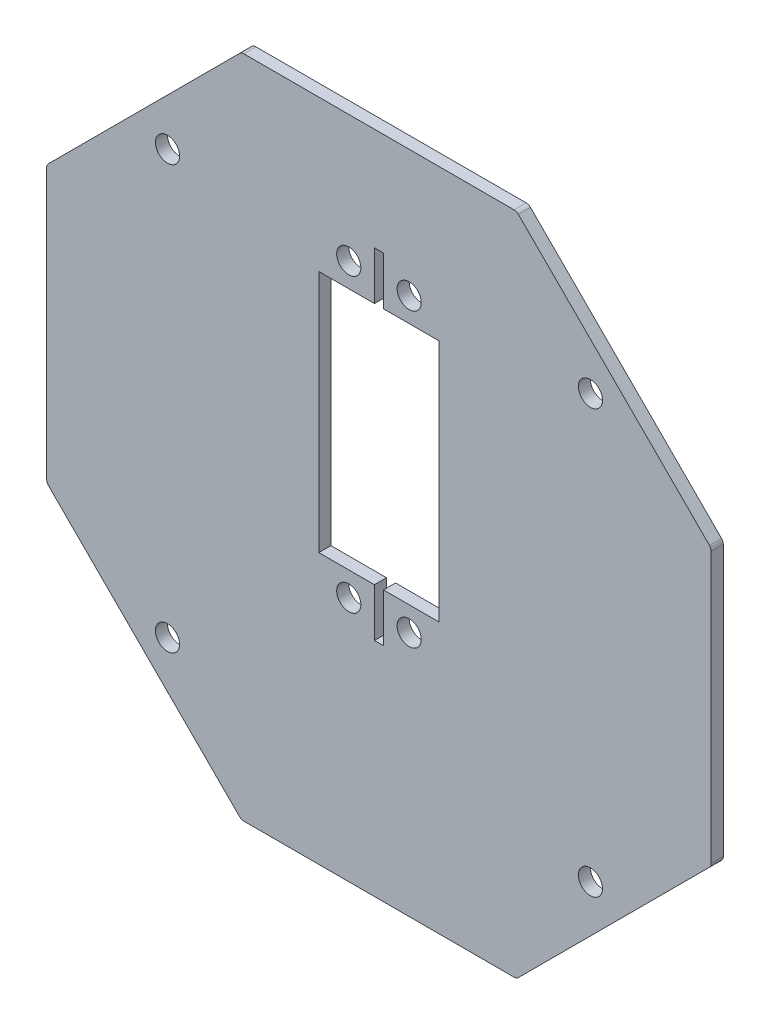
SolidWorks part; units mm, degrees
ref_plane "前视基准面" through (0, 0, 0) normal (0, 0, 1) x (1, 0, 0)
ref_plane "上视基准面" through (0, 0, 0) normal (0, 1, 0) x (1, 0, 0)
ref_plane "右视基准面" through (0, 0, 0) normal (1, 0, 0) x (0, 0, -1)
sketch "Model" plane through (0, 0, 0) normal (0, 0, 1) x (1, 0, 0)
  line L0 (2535.9672, 1984.4919) -> (2534.6672, 1984.4919)
  line L1 (2534.6672, 1984.4919) -> (2534.6672, 1976.4919)
  line L2 (2534.6672, 1976.4919) -> (2525.3578, 1976.4919)
  line L3 (2525.3578, 1976.4919) -> (2525.3578, 1936.1919)
  line L4 (2525.3578, 1936.1919) -> (2534.6672, 1936.1919)
  line L5 (2534.6672, 1936.1919) -> (2534.6672, 1928.1919)
  line L6 (2534.6672, 1928.1919) -> (2535.9672, 1928.1919)
  line L7 (2535.9672, 1928.1919) -> (2535.9672, 1936.1919)
  line L8 (2535.9672, 1936.1919) -> (2545.2767, 1936.1919)
  line L9 (2545.2767, 1936.1919) -> (2545.2767, 1976.4919)
  line L10 (2545.2767, 1976.4919) -> (2535.9672, 1976.4919)
  line L11 (2535.9672, 1976.4919) -> (2535.9672, 1984.4919)
  line L12 (2512.2426, 2001.1966) -> (2480.6101, 1969.5642)
  line L13 (2480.3172, 1968.857) -> (2480.3172, 1924.122)
  line L14 (2480.6101, 1923.4149) -> (2512.2426, 1891.7824)
  line L15 (2512.9497, 1891.4895) -> (2557.6848, 1891.4895)
  line L16 (2558.3919, 1891.7824) -> (2590.0243, 1923.4149)
  line L17 (2590.3172, 1924.122) -> (2590.3172, 1968.857)
  line L18 (2590.0243, 1969.5642) -> (2558.3919, 2001.1966)
  line L19 (2557.6848, 2001.4895) -> (2512.9497, 2001.4895)
  circle A0 centre (2500.3154, 1911.4877) radius 2
  circle A1 centre (2570.319, 1981.4913) radius 2
  circle A2 centre (2530.3172, 1980.4969) radius 2
  circle A3 centre (2540.3172, 1932.1969) radius 2
  circle A4 centre (2540.3172, 1980.4969) radius 2
  circle A5 centre (2500.3154, 1981.4913) radius 2
  circle A6 centre (2570.319, 1911.4877) radius 2
  circle A7 centre (2530.3172, 1932.1969) radius 2
  arc A8 (2480.6101, 1969.5642) -> (2480.3172, 1968.857) centre (2481.3172, 1968.857) ccw
  arc A9 (2480.3172, 1924.122) -> (2480.6101, 1923.4149) centre (2481.3172, 1924.122) ccw
  arc A10 (2512.2426, 1891.7824) -> (2512.9497, 1891.4895) centre (2512.9497, 1892.4895) ccw
  arc A11 (2557.6848, 1891.4895) -> (2558.3919, 1891.7824) centre (2557.6848, 1892.4895) ccw
  arc A12 (2590.0243, 1923.4149) -> (2590.3172, 1924.122) centre (2589.3172, 1924.122) ccw
  arc A13 (2590.3172, 1968.857) -> (2590.0243, 1969.5642) centre (2589.3172, 1968.857) ccw
  arc A14 (2558.3919, 2001.1966) -> (2557.6848, 2001.4895) centre (2557.6848, 2000.4895) ccw
  arc A15 (2512.9497, 2001.4895) -> (2512.2426, 2001.1966) centre (2512.9497, 2000.4895) ccw
  spline S0 degree 3 poles (0, 0) (0.3333, 0) (0.6667, 0) (1, 0) knots 0 0 0 0 1 1 1 1
extrude "凸台-拉伸1" add sketch "Model" along normal blind 2 contours L19 A15 L12 A8 L13 A9 L14 A10 L15 A11 L16 A12 L17 A13 L18 A14 L11 L10 L9 L8 L7 L6 L5 L4 L3 L2 L1 L0 A0 A1 A2 A3 A4 A5 A6 A7
sketch "草图3" plane through (0, 0, 2) normal (0, 0, 1) x (1, 0, 0)
  line L0 (2535.9672, 1936.1919) -> (2536.0672, 1936.1919)
  line L1 (2535.9672, 1936.1919) -> (2545.2767, 1936.1919) construction
  line L2 (2536.0672, 1936.1919) -> (2536.0672, 1928.1919)
  line L3 (2536.0672, 1928.1919) -> (2535.9672, 1928.1919)
  line L4 (2535.9672, 1928.1919) -> (2535.9672, 1936.1919)
  line L5 (2534.6672, 1936.1919) -> (2534.6672, 1928.1919)
  line L6 (2534.6672, 1928.1919) -> (2534.5672, 1928.1919)
  line L7 (2534.5672, 1928.1919) -> (2534.5672, 1936.1919)
  line L8 (2525.3578, 1936.1919) -> (2534.6672, 1936.1919) construction
  line L9 (2534.5672, 1936.1919) -> (2534.6672, 1936.1919)
extrude "切除-拉伸1" cut sketch "草图3" against normal blind 2
sketch "草图6" plane through (0, 0, 2) normal (0, 0, 1) x (1, 0, 0)
  line L0 (2535.9672, 1976.4919) -> (2536.0672, 1976.4919)
  line L1 (2545.2767, 1976.4919) -> (2535.9672, 1976.4919) construction
  line L2 (2536.0672, 1976.4919) -> (2536.0672, 1984.4919)
  line L3 (2536.0672, 1984.4919) -> (2535.9672, 1984.4919)
  line L4 (2535.9672, 1984.4919) -> (2535.9672, 1976.4919)
  line L5 (2534.6672, 1976.4919) -> (2534.5672, 1976.4919)
  line L6 (2534.6672, 1976.4919) -> (2525.3578, 1976.4919) construction
  line L7 (2534.5672, 1976.4919) -> (2534.5672, 1984.4919)
  line L8 (2534.5672, 1984.4919) -> (2534.6672, 1984.4919)
  line L9 (2534.6672, 1984.4919) -> (2534.6672, 1976.4919)
extrude "切除-拉伸2" cut sketch "草图6" against normal blind 2
